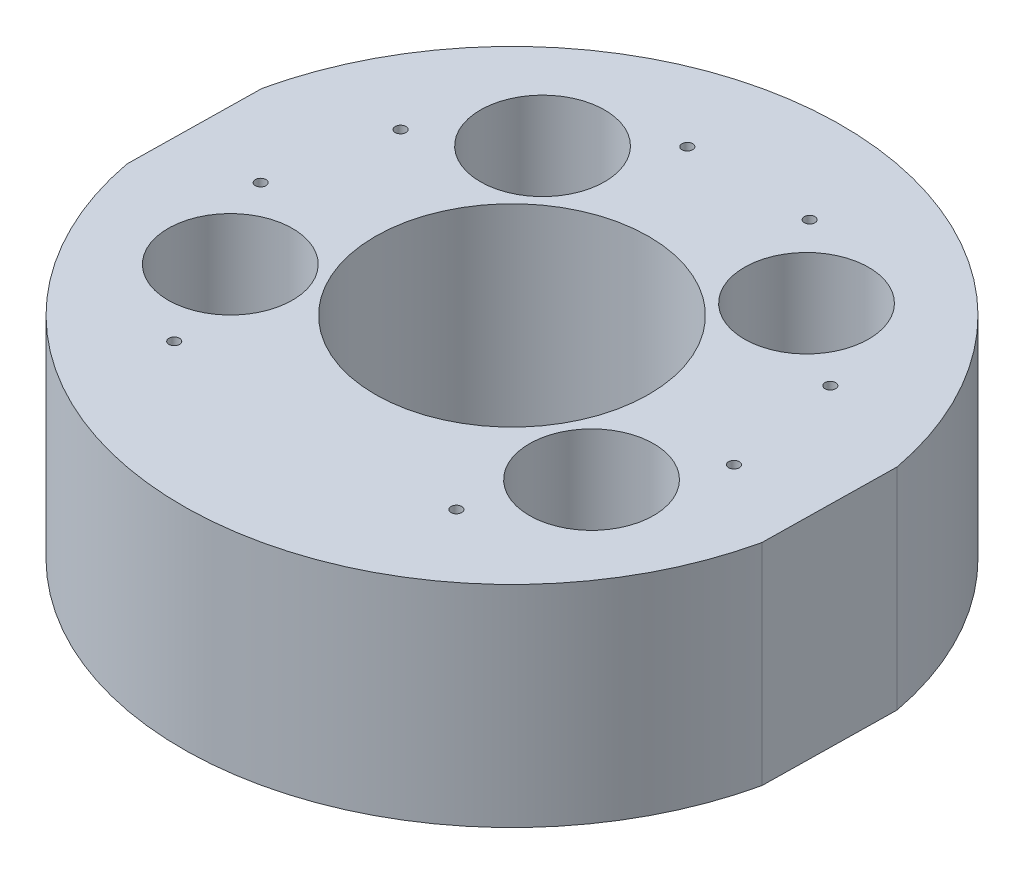
SolidWorks part; units mm, degrees
material "ABS"
ref_plane "Front Plane" through (0, 0, 0) normal (0, 0, 1) x (1, 0, 0)
ref_plane "Top Plane" through (0, 0, 0) normal (0, 1, 0) x (1, 0, 0)
ref_plane "Right Plane" through (0, 0, 0) normal (1, 0, 0) x (0, 0, -1)
sketch "Sketch1" plane through (0, 0, 0) normal (0, 1, 0) x (0.9999, 0, -0.0151)
  line L2 (-61.1695, 13.237) -> (-61.9456, -11.7509)
  line L3 (59.8522, 9.4781) -> (59.0761, -15.5098)
  circle A0 centre (-1.0467, -1.1364) radius 25.667
  arc A1 (59.8522, 9.4781) -> (-61.1695, 13.237) centre (-1.0467, -1.1364) ccw
  circle A2 centre (-25.2705, 29.6476) radius 11.666
  circle A3 centre (25.0408, 28.085) radius 11.666
  circle A4 centre (32.7953, -20.8636) radius 11.666
  circle A5 centre (-36.0477, -18.7254) radius 11.666
  arc A6 (-61.9456, -11.7509) -> (59.0761, -15.5098) centre (-1.0467, -1.1364) ccw
  dimension "D1" = 23.332
  dimension "D2" = 23.332
  dimension "D3" = 23.332
  dimension "D4" = 23.332
extrude "Boss-Extrude1" add sketch "Sketch1" along normal blind 39.5
extrude "Cut-Extrude1" cut sketch "Sketch2" against normal blind 8
sketch "Sketch2" plane through (-5.1081, 39.5, 5.9057) normal (0, 1, 0) x (0.9999, 0, 0.016)
  circle A0 centre (-13.0987, 51.8027) radius 1
  circle A1 centre (21.1033, 51.8027) radius 1
  circle A2 centre (40.6503, 18.1569) radius 1
  circle A3 centre (55.5443, -5.1203) radius 1
  circle A4 centre (20.5093, -31.747) radius 1
  circle A5 centre (-12.5047, -31.747) radius 1
  circle A6 centre (-47.5397, -5.1203) radius 1
  circle A7 centre (-32.6457, 18.1569) radius 1
extrude "Cut-Extrude2" cut sketch "Sketch3" against normal blind 12
sketch "Sketch3" plane through (-5.1081, 40.5, 5.9057) normal (0, 1, 0) x (0.9999, 0, 0.016)
  circle A0 centre (-7.6628, 48.4869) radius 1
  circle A1 centre (15.6674, 48.4869) radius 1
  circle A2 centre (44.9674, 23.9204) radius 1
  circle A3 centre (49.1209, 2.1076) radius 1
  circle A4 centre (30.8998, -31.5077) radius 1
  circle A5 centre (-22.8952, -31.5077) radius 1
  circle A6 centre (-41.1164, 2.1076) radius 1
  circle A7 centre (-36.9628, 23.9204) radius 1
